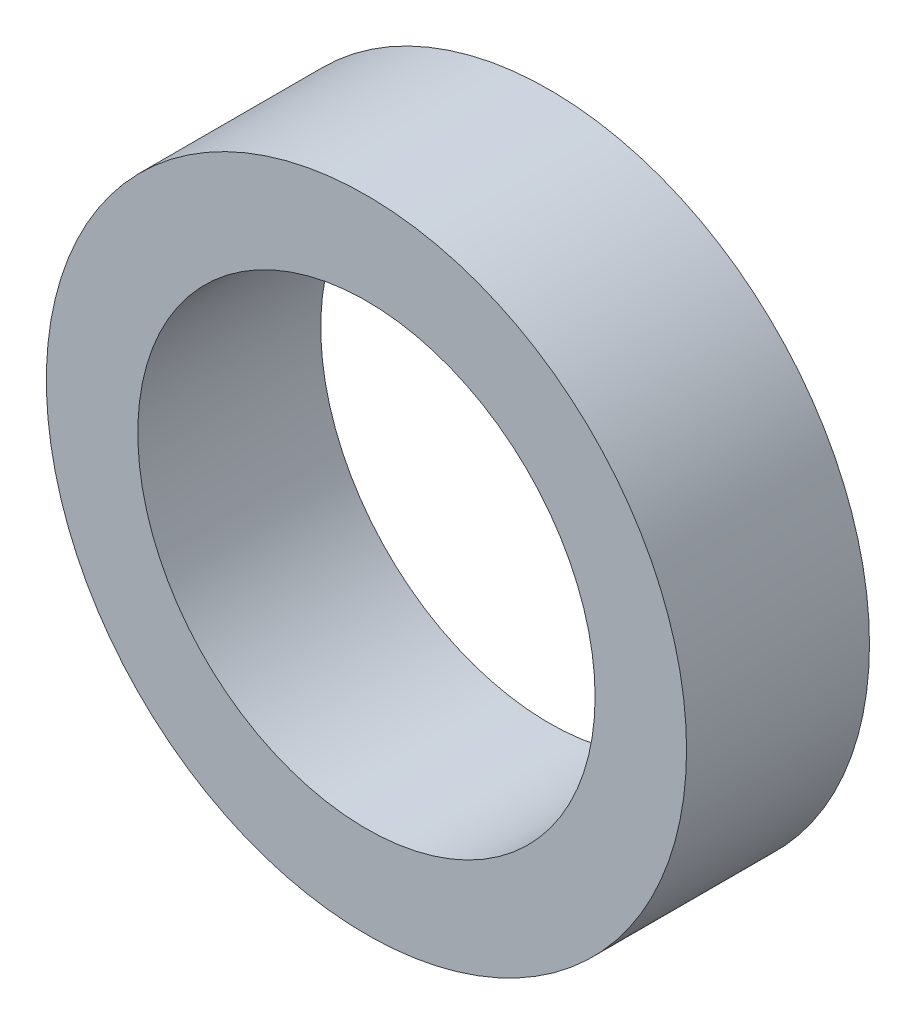
SolidWorks part; units mm, degrees
ref_plane "前视基准面" through (0, 0, 0) normal (0, 0, 1) x (1, 0, 0)
ref_plane "上视基准面" through (0, 0, 0) normal (0, 1, 0) x (1, 0, 0)
ref_plane "右视基准面" through (0, 0, 0) normal (1, 0, 0) x (0, 0, -1)
sketch "草图1" plane through (0, 0, 0) normal (0, 0, 1) x (1, 0, 0)
  circle A0 centre (0, 0) radius 5
  circle A1 centre (0, 0) radius 7
  dimension "D1" = 10
  dimension "D2" = 14
extrude "凸台-拉伸1" add sketch "草图1" along normal blind 4
